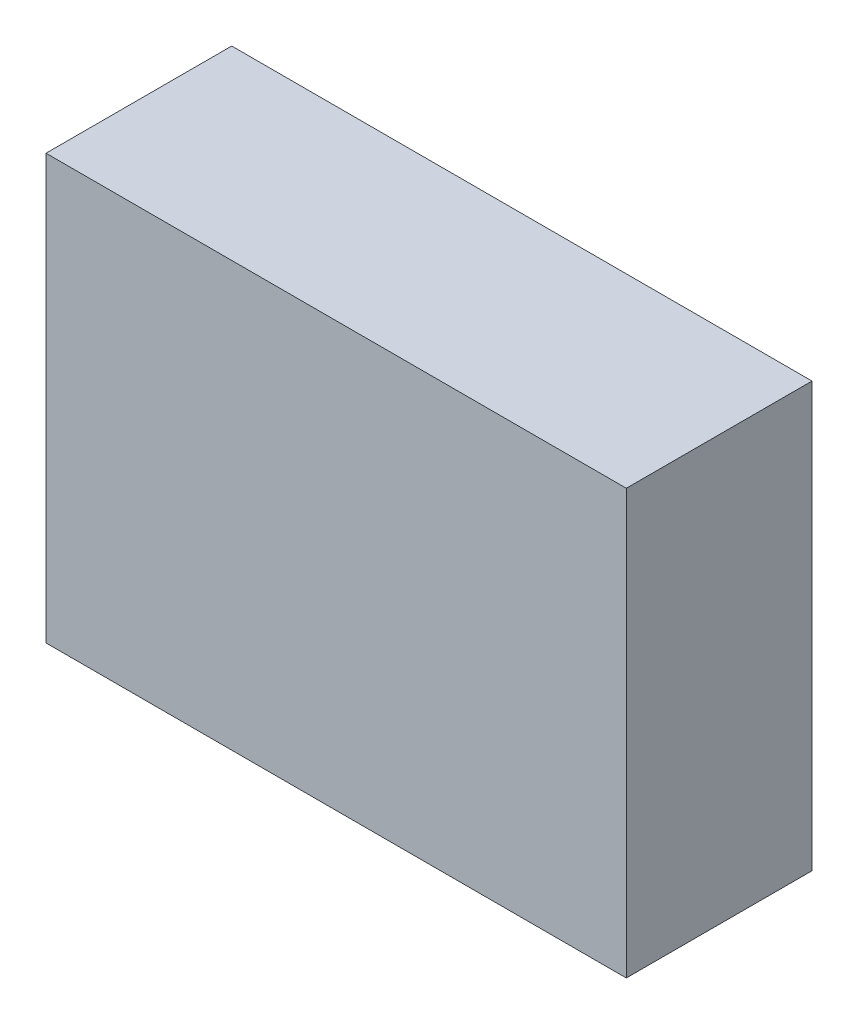
SolidWorks part; units mm, degrees
ref_plane "Front Plane" through (0, 0, 0) normal (1, 0, 0) x (0, 1, 0)
ref_plane "Top Plane" through (0, 0, 0) normal (0, 0, 1) x (0, 1, 0)
ref_plane "Right Plane" through (0, 0, 0) normal (0, 1, 0) x (-1, 0, 0)
sketch "Sketch1" plane through (0, 0, 0) normal (0, 0, 1) x (0, 1, 0)
  line L1 (0, 0) -> (40.2, 0)
  line L2 (0, 0) -> (0, 55)
  line L3 (0, 55) -> (40.2, 55)
  line L4 (40.2, 0) -> (40.2, 55)
  dimension "D1" = 55
  dimension "D2" = 40.2
extrude "Boss-Extrude1" add sketch "Sketch1" along normal blind 17.6
